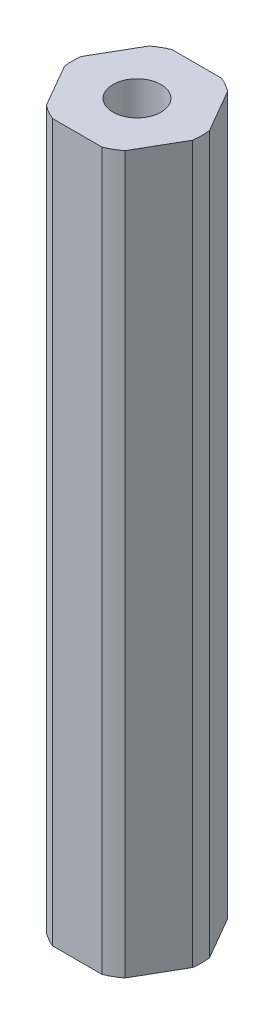
SolidWorks part; units mm, degrees
ref_plane "Front" through (0, 0, 0) normal (0, 0, 1) x (1, 0, 0)
ref_plane "Top" through (0, 0, 0) normal (0, 1, 0) x (1, 0, 0)
ref_plane "Right" through (0, 0, 0) normal (1, 0, 0) x (0, 0, -1)
sketch "Sketch1" plane through (0, 0, 0) normal (0, 1, 0) x (1, 0, 0)
  line L1 (3.6662, -6.35) -> (7.3323, 0)
  line L2 (7.3323, 0) -> (3.6662, 6.35)
  line L3 (3.6662, 6.35) -> (-3.6662, 6.35)
  line L4 (-3.6662, 6.35) -> (-7.3323, 0)
  line L5 (-7.3323, 0) -> (-3.6662, -6.35)
  line L6 (-3.6662, -6.35) -> (3.6662, -6.35)
  circle A0 centre (0, 0) radius 6.35 construction
  circle A1 centre (0, 0) radius 6.8758
  circle A2 centre (0, 0) radius 2.5527
  dimension "D2" = 13.7516
  dimension "D3" = 5.1054
  dimension "D1" = 12.7
extrude "Boss-Extrude1" add sketch "Sketch1" along normal mid plane 76.2 contours L6 A1 L1 L2 L3 L4 L5 A2
